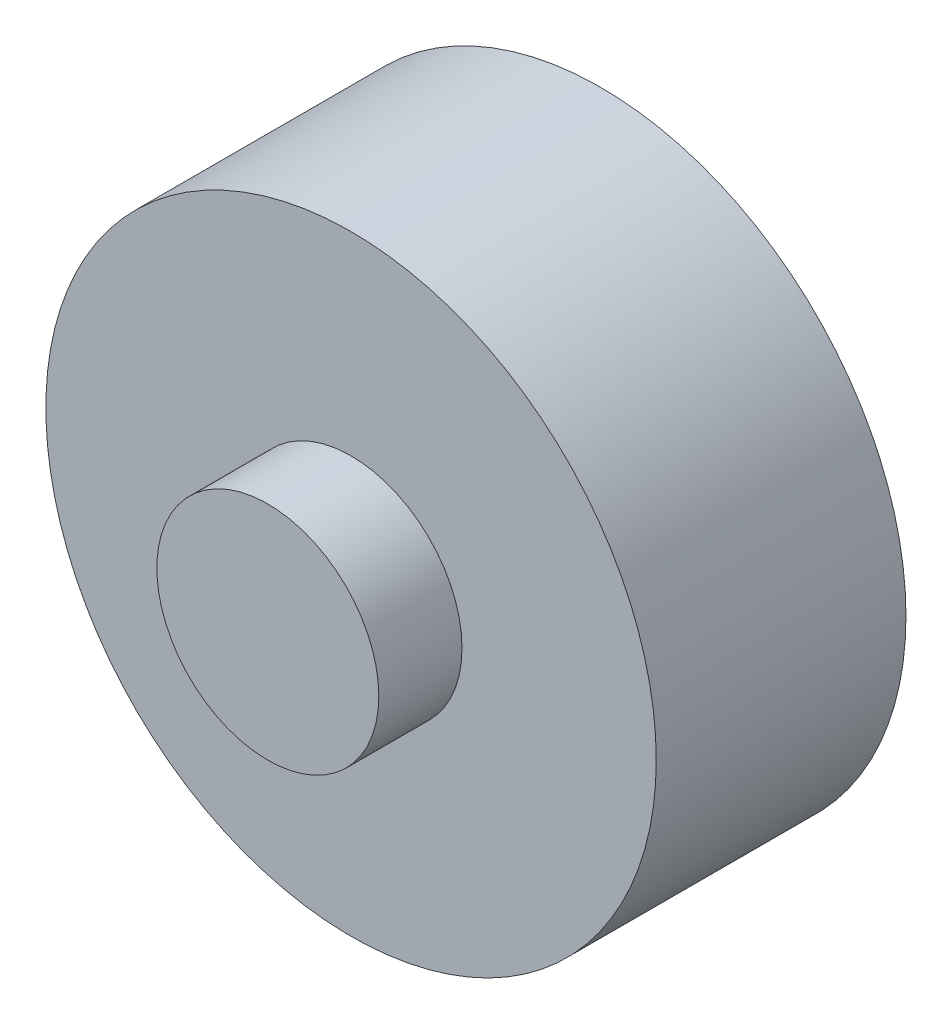
SolidWorks part; units mm, degrees
ref_plane "前视基准面" through (0, 0, 0) normal (0, 0, 1) x (1, 0, 0)
ref_plane "上视基准面" through (0, 0, 0) normal (0, 1, 0) x (1, 0, 0)
ref_plane "右视基准面" through (0, 0, 0) normal (1, 0, 0) x (0, 0, -1)
other "Configuration Table"
sketch "草图1" plane through (0, 0, 0) normal (0, 0, 1) x (1, 0, 0)
  circle A0 centre (0, 0) radius 8
extrude "凸台-拉伸1" add sketch "草图1" along normal blind 24
sketch "草图2" plane through (0, 0, 0) normal (0, 0, 1) x (1, 0, 0)
  circle A0 centre (0, 0) radius 22
extrude "凸台-拉伸2" add sketch "草图2" along normal blind 18
sketch "草图3" plane through (0, 0, 0) normal (0, 0, -1) x (-1, 0, 0)
  circle A0 centre (0, 0) radius 22
sketch "草图4" plane through (0, 0, 0) normal (0, 0, 1) x (1, 0, 0)
  circle A0 centre (0, 0) radius 8
extrude "凸台-拉伸3" add sketch "草图4" along normal blind 6
sketch "草图5" plane through (0, 0, 24) normal (0, 0, 1) x (1, 0, 0)
  line L0 (-4.8339, 1.6257) -> (4.5201, 2.3619)
  arc A0 (4.5201, 2.3619) -> (-4.8339, 1.6257) centre (0, 0) cw
sketch "草图6" plane through (0, 0, 24) normal (0, 0, 1) x (1, 0, 0)
  line L0 (17.4237, 1.6329) -> (18.7119, 1.6329)
  line L1 (18.3379, 4.1145) -> (17.4237, 4.1145)
  arc A0 (21.989, 0.6948) -> (21.1275, 6.1342) centre (0, 0) ccw
  arc A1 (17.4237, 4.1145) -> (17.8248, 1.6705) centre (0, 0) cw
sketch "草图7" plane through (0, 0, 24) normal (0, 0, 1) x (1, 0, 0)
  line L0 (16.0663, 6.9372) -> (17.2541, 7.4501)
  line L1 (16.0663, 9.5798) -> (15.0307, 8.9624)
  arc A0 (20.6981, 7.4501) -> (18.1963, 12.3617) centre (0, 0) ccw
  arc A1 (15.0307, 8.9624) -> (16.0662, 6.9372) centre (0, 0) cw
sketch "草图8" plane through (0, 0, 24) normal (0, 0, 1) x (1, 0, 0)
  line L0 (13.1362, 11.5624) -> (14.0493, 12.4754)
  line L1 (12.4173, 14.1075) -> (11.5624, 13.1362)
  arc A0 (17.3811, 13.4869) -> (13.4869, 17.3811) centre (0, 0) ccw
  arc A1 (11.5624, 13.1362) -> (13.1362, 11.5624) centre (0, 0) cw
sketch "草图9" plane through (0, 0, 24) normal (0, 0, 1) x (1, 0, 0)
  line L0 (8.9203, 15.0558) -> (9.8067, 15.9422)
  line L1 (7.4557, 17.2541) -> (6.8888, 15.9422)
  arc A0 (12.3627, 18.1979) -> (7.4557, 20.6981) centre (0, 0) ccw
  arc A1 (6.8888, 15.9422) -> (8.8525, 14.9413) centre (0, 0) cw
sketch "草图10" plane through (0, 0, 24) normal (0, 0, 1) x (1, 0, 0)
  line L0 (3.8312, 17.0755) -> (3.8312, 18.3379)
  line L1 (1.7536, 18.7119) -> (1.7536, 17.0755)
  arc A0 (6.1342, 21.1275) -> (0.6948, 21.989) centre (0, 0) ccw
  arc A1 (1.7536, 17.0755) -> (3.758, 16.7489) centre (0, 0) cw
sketch "草图11" plane through (0, 0, 24) normal (0, 0, 1) x (1, 0, 0)
  line L0 (-1.6329, 17.4237) -> (-1.6329, 18.7119)
  line L1 (-4.1145, 18.3379) -> (-4.1145, 17.4237)
  arc A0 (-0.6948, 21.989) -> (-6.1342, 21.1275) centre (0, 0) ccw
  arc A1 (-4.1145, 17.4237) -> (-1.6705, 17.8248) centre (0, 0) cw
sketch "草图12" plane through (0, 0, 24) normal (0, 0, 1) x (1, 0, 0)
  line L0 (-6.9372, 16.0663) -> (-7.4501, 17.2541)
  line L1 (-9.5798, 16.0663) -> (-8.9624, 15.0307)
  arc A0 (-7.4501, 20.6981) -> (-12.3617, 18.1963) centre (0, 0) ccw
  arc A1 (-8.9624, 15.0307) -> (-6.9372, 16.0662) centre (0, 0) cw
sketch "草图13" plane through (0, 0, 24) normal (0, 0, 1) x (1, 0, 0)
  line L0 (-11.5624, 13.1362) -> (-12.4754, 14.0493)
  line L1 (-14.1075, 12.4173) -> (-13.1362, 11.5624)
  arc A0 (-13.4869, 17.3811) -> (-17.3811, 13.4869) centre (0, 0) ccw
  arc A1 (-13.1362, 11.5624) -> (-11.5624, 13.1362) centre (0, 0) cw
sketch "草图14" plane through (0, 0, 24) normal (0, 0, 1) x (1, 0, 0)
  line L0 (-15.0558, 8.9203) -> (-15.9422, 9.8067)
  line L1 (-17.2541, 7.4557) -> (-15.9422, 6.8888)
  arc A0 (-18.1979, 12.3627) -> (-20.6981, 7.4557) centre (0, 0) ccw
  arc A1 (-15.9422, 6.8888) -> (-14.9413, 8.8525) centre (0, 0) cw
sketch "草图15" plane through (0, 0, 24) normal (0, 0, 1) x (1, 0, 0)
  line L0 (-17.0755, 3.8312) -> (-18.3379, 3.8312)
  line L1 (-18.7119, 1.7536) -> (-17.0755, 1.7536)
  arc A0 (-21.1275, 6.1342) -> (-21.989, 0.6948) centre (0, 0) ccw
  arc A1 (-17.0755, 1.7536) -> (-16.7489, 3.758) centre (0, 0) cw
sketch "草图16" plane through (0, 0, 24) normal (0, 0, 1) x (1, 0, 0)
  line L0 (-17.4237, -1.6329) -> (-18.7119, -1.6329)
  line L1 (-18.3379, -4.1145) -> (-17.4237, -4.1145)
  arc A0 (-21.989, -0.6948) -> (-21.1275, -6.1342) centre (0, 0) ccw
  arc A1 (-17.4237, -4.1145) -> (-17.8248, -1.6705) centre (0, 0) cw
sketch "草图17" plane through (0, 0, 24) normal (0, 0, 1) x (1, 0, 0)
  line L0 (-16.0663, -6.9372) -> (-17.2541, -7.4501)
  line L1 (-16.0663, -9.5798) -> (-15.0307, -8.9624)
  arc A0 (-20.6981, -7.4501) -> (-18.1963, -12.3617) centre (0, 0) ccw
  arc A1 (-15.0307, -8.9624) -> (-16.0662, -6.9372) centre (0, 0) cw
sketch "草图18" plane through (0, 0, 24) normal (0, 0, 1) x (1, 0, 0)
  line L0 (-13.1362, -11.5624) -> (-14.0493, -12.4754)
  line L1 (-12.4173, -14.1075) -> (-11.5624, -13.1362)
  arc A0 (-17.3811, -13.4869) -> (-13.4869, -17.3811) centre (0, 0) ccw
  arc A1 (-11.5624, -13.1362) -> (-13.1362, -11.5624) centre (0, 0) cw
sketch "草图19" plane through (0, 0, 24) normal (0, 0, 1) x (1, 0, 0)
  line L0 (-8.9203, -15.0558) -> (-9.8067, -15.9422)
  line L1 (-7.4557, -17.2541) -> (-6.8888, -15.9422)
  arc A0 (-12.3627, -18.1979) -> (-7.4557, -20.6981) centre (0, 0) ccw
  arc A1 (-6.8888, -15.9422) -> (-8.8525, -14.9413) centre (0, 0) cw
sketch "草图20" plane through (0, 0, 24) normal (0, 0, 1) x (1, 0, 0)
  line L0 (-3.8312, -17.0755) -> (-3.8312, -18.3379)
  line L1 (-1.7536, -18.7119) -> (-1.7536, -17.0755)
  arc A0 (-6.1342, -21.1275) -> (-0.6948, -21.989) centre (0, 0) ccw
  arc A1 (-1.7536, -17.0755) -> (-3.758, -16.7489) centre (0, 0) cw
sketch "草图21" plane through (0, 0, 24) normal (0, 0, 1) x (1, 0, 0)
  line L0 (1.6329, -17.4237) -> (1.6329, -18.7119)
  line L1 (4.1145, -18.3379) -> (4.1145, -17.4237)
  arc A0 (0.6948, -21.989) -> (6.1342, -21.1275) centre (0, 0) ccw
  arc A1 (4.1145, -17.4237) -> (1.6705, -17.8248) centre (0, 0) cw
sketch "草图22" plane through (0, 0, 24) normal (0, 0, 1) x (1, 0, 0)
  line L0 (6.9372, -16.0663) -> (7.4501, -17.2541)
  line L1 (9.5798, -16.0663) -> (8.9624, -15.0307)
  arc A0 (7.4501, -20.6981) -> (12.3617, -18.1963) centre (0, 0) ccw
  arc A1 (8.9624, -15.0307) -> (6.9372, -16.0662) centre (0, 0) cw
sketch "草图23" plane through (0, 0, 24) normal (0, 0, 1) x (1, 0, 0)
  line L0 (11.5624, -13.1362) -> (12.4754, -14.0493)
  line L1 (14.1075, -12.4173) -> (13.1362, -11.5624)
  arc A0 (13.4869, -17.3811) -> (17.3811, -13.4869) centre (0, 0) ccw
  arc A1 (13.1362, -11.5624) -> (11.5624, -13.1362) centre (0, 0) cw
sketch "草图24" plane through (0, 0, 24) normal (0, 0, 1) x (1, 0, 0)
  line L0 (15.0558, -8.9203) -> (15.9422, -9.8067)
  line L1 (17.2541, -7.4557) -> (15.9422, -6.8888)
  arc A0 (18.1979, -12.3627) -> (20.6981, -7.4557) centre (0, 0) ccw
  arc A1 (15.9422, -6.8888) -> (14.9413, -8.8525) centre (0, 0) cw
sketch "草图25" plane through (0, 0, 24) normal (0, 0, 1) x (1, 0, 0)
  line L0 (17.0755, -3.8312) -> (18.3379, -3.8312)
  line L1 (18.7119, -1.7536) -> (17.0755, -1.7536)
  arc A0 (21.1275, -6.1342) -> (21.989, -0.6948) centre (0, 0) ccw
  arc A1 (17.0755, -1.7536) -> (16.7489, -3.758) centre (0, 0) cw
